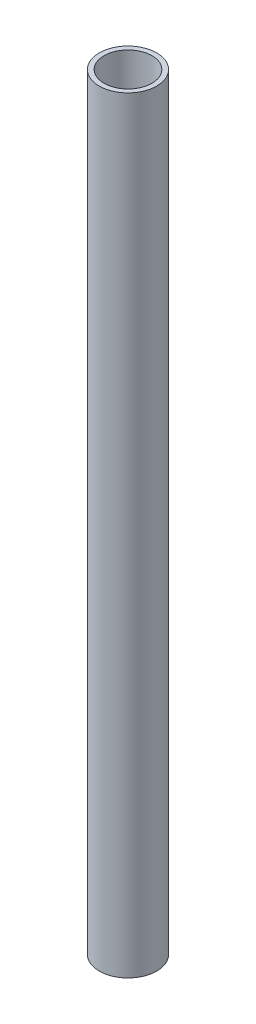
SolidWorks part; units mm, degrees
ref_plane "Front Plane" through (0, 0, 0) normal (0, 0, 1) x (1, 0, 0)
ref_plane "Top Plane" through (0, 0, 0) normal (0, 1, 0) x (1, 0, 0)
ref_plane "Right Plane" through (0, 0, 0) normal (1, 0, 0) x (0, 0, -1)
sketch "Sketch1" plane through (0, 0, 0) normal (0, 1, 0) x (1, 0, 0)
  circle A0 centre (0, 0) radius 3.81
  circle A1 centre (0, 0) radius 3.175
  dimension "D1" = 7.62
  dimension "D2" = 6.35
extrude "Boss-Extrude1" add sketch "Sketch1" along normal blind 101.6
